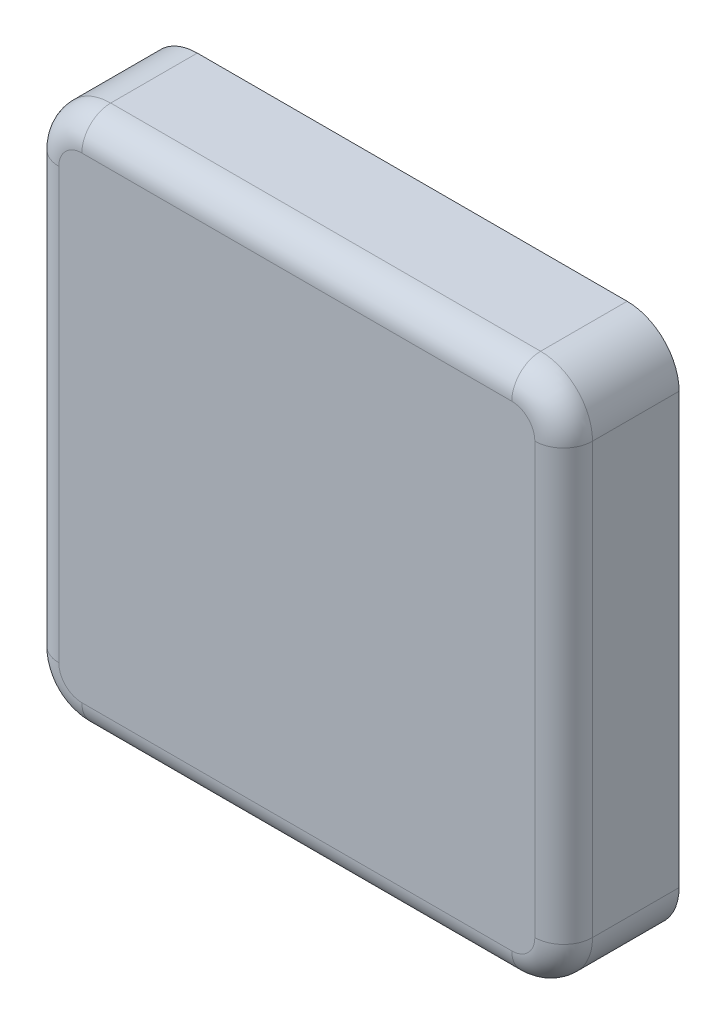
SolidWorks part; units mm, degrees
ref_plane "Piano frontale" through (0, 0, 0) normal (0, 0, 1) x (1, 0, 0)
ref_plane "Piano superiore" through (0, 0, 0) normal (0, 1, 0) x (1, 0, 0)
ref_plane "Piano destro" through (0, 0, 0) normal (1, 0, 0) x (0, 0, -1)
sketch "Schizzo1" plane through (0, 0, 0) normal (0, 0, 1) x (1, 0, 0)
  line L1 (-9.25, -9.25) -> (9.25, -9.25)
  line L2 (-9.25, -9.25) -> (-9.25, 9.25)
  line L3 (-9.25, 9.25) -> (9.25, 9.25)
  line L4 (9.25, -9.25) -> (9.25, 9.25)
  line L5 (-9.25, -9.25) -> (9.25, 9.25) construction
  line L6 (-9.25, 9.25) -> (9.25, -9.25) construction
  point P0 (0, 0)
  dimension "D1" = 18.5
extrude "Estrusione-Estrusione1" add sketch "Schizzo1" along normal blind 4
fillet "Raccordo1" radius 1.8 4 edges at (-9.25, 9.25, 2) (-9.25, -9.25, 2) (9.25, -9.25, 2) (9.25, 9.25, 2)
fillet "Raccordo2" radius 1 8 edges at (8.7228, 8.7228, 4) (9.25, 0, 4) (8.7228, -8.7228, 4) (0, -9.25, 4) (-8.7228, -8.7228, 4) (-9.25, 0, 4) (-8.7228, 8.7228, 4) (0, 9.25, 4)
shell "Svuota1" thickness 2
chamfer "Smusso1" distance 1.4 angle 45 4 edges at (-7.25, 0, 0) (0, 7.25, 0) (7.25, 0, 0) (0, -7.25, 0)
